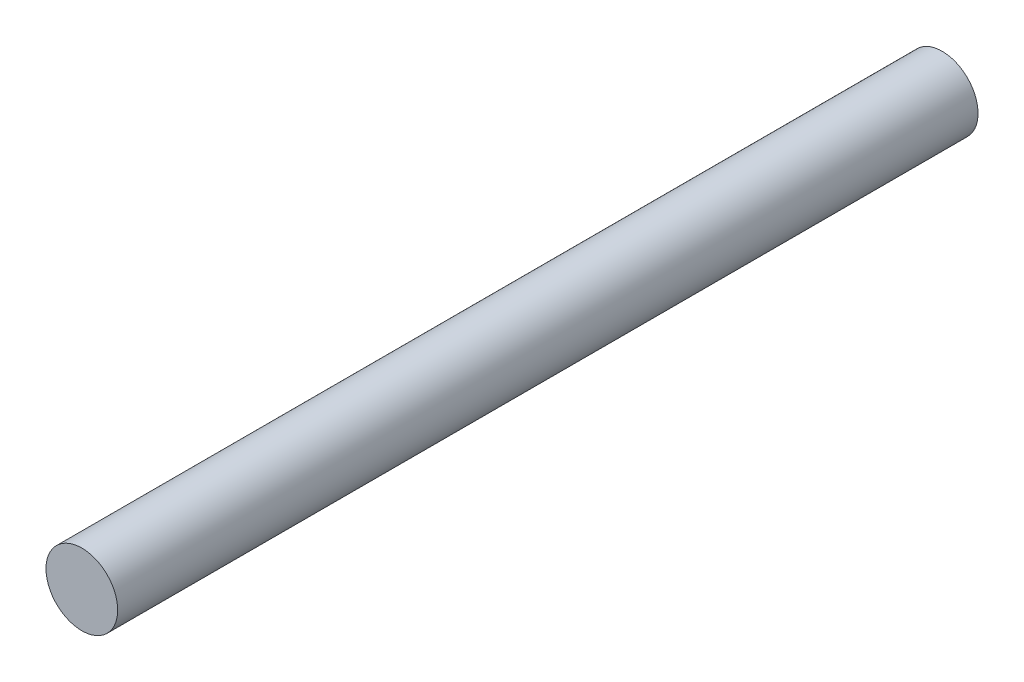
SolidWorks part; units mm, degrees
ref_plane "Front Plane" through (0, 0, 0) normal (0, 0, 1) x (1, 0, 0)
ref_plane "Top Plane" through (0, 0, 0) normal (0, 1, 0) x (1, 0, 0)
ref_plane "Right Plane" through (0, 0, 0) normal (1, 0, 0) x (0, 0, -1)
sketch "Sketch1" plane through (0, 0, 0) normal (0, 0, 1) x (1, 0, 0)
  circle A0 centre (0, 0) radius 12.7
  dimension "D1" = 25.4
extrude "Boss-Extrude1" add sketch "Sketch1" along normal blind 304.8
